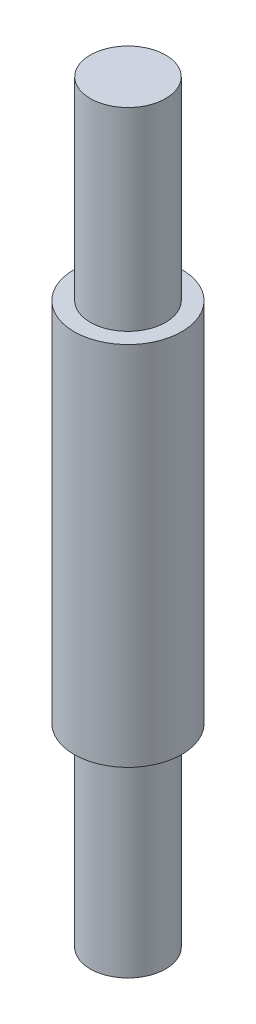
SolidWorks part; units mm, degrees
ref_plane "Front Plane" through (0, 0, 0) normal (0, 0, 1) x (1, 0, 0)
ref_plane "Top Plane" through (0, 0, 0) normal (0, 1, 0) x (1, 0, 0)
ref_plane "Right Plane" through (0, 0, 0) normal (1, 0, 0) x (0, 0, -1)
sketch "Sketch1" plane through (0, 0, 0) normal (0, 0, 1) x (1, 0, 0)
  line L0 (0, 0) -> (0, 88.9) construction
  line L1 (-4.445, 0) -> (-4.445, 22.86)
  line L2 (-4.445, 22.86) -> (-6.35, 22.86)
  line L3 (-6.35, 22.86) -> (-6.35, 66.04)
  line L4 (-6.35, 66.04) -> (-4.445, 66.04)
  line L5 (-4.445, 66.04) -> (-4.445, 88.9)
  line L6 (-4.445, 88.9) -> (0, 88.9)
  line L7 (-4.445, 0) -> (0, 0)
  line L8 (0, 88.9) -> (0, 0)
  dimension "D1" = 88.9
  dimension "D2" = 4.445
  dimension "D3" = 8.89
  dimension "D4" = 6.35
  dimension "D5" = 22.86
  dimension "D6" = 22.86
revolve "Revolve1" add sketch "Sketch1" angle 360 about L8
